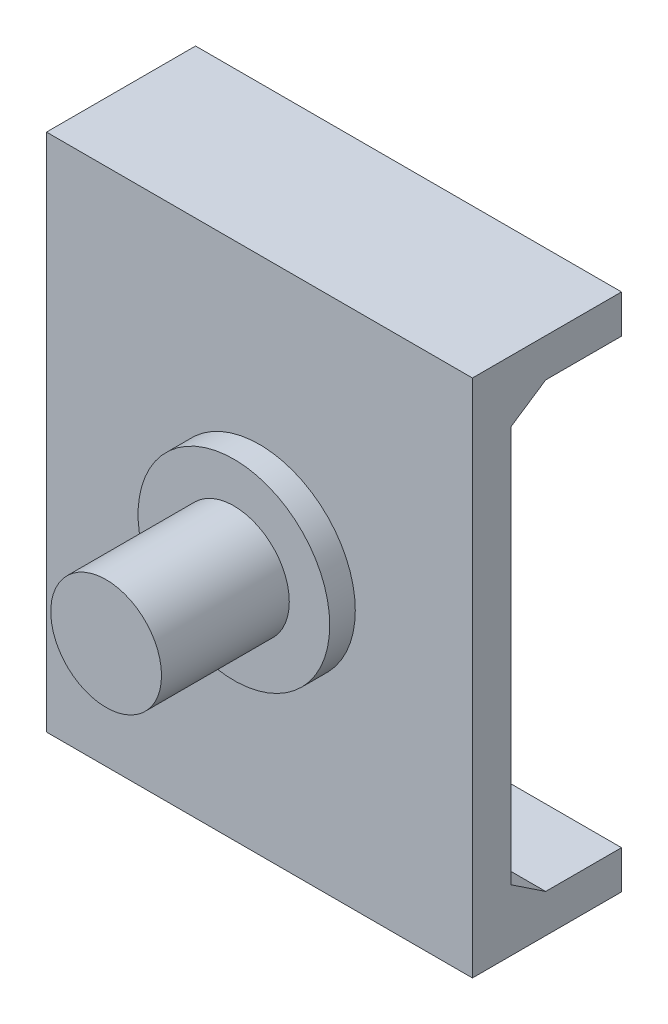
SolidWorks part; units mm, degrees
material "PETG"
ref_plane "Front Plane" through (0, 0, 0) normal (0, 0, 1) x (1, 0, 0)
ref_plane "Top Plane" through (0, 0, 0) normal (0, 1, 0) x (1, 0, 0)
ref_plane "Right Plane" through (0, 0, 0) normal (1, 0, 0) x (0, 0, -1)
sketch "Sketch1" plane through (0, 0, 0) normal (0, 0, 1) x (1, 0, 0)
  line L1 (-10, -12.2) -> (10, -12.2)
  line L2 (-10, -12.2) -> (-10, 12.2)
  line L3 (-10, 12.2) -> (10, 12.2)
  line L4 (10, -12.2) -> (10, 12.2)
  line L5 (-10, -12.2) -> (10, 12.2) construction
  line L6 (-10, 12.2) -> (10, -12.2) construction
  point P0 (0, 0)
  dimension "D2" = 20
extrude "Boss-Extrude1" add sketch "Sketch1" against normal blind 5 and the other way blind 2
sketch "Sketch3" plane through (10, 0, 0) normal (1, 0, 0) x (0, 0, -1)
  line L0 (1.5, 10.2) -> (8, 10.2) construction
  line L1 (1.5, 10.2) -> (0, 9.2) construction
  line L2 (0, 7.95) -> (0, 9.2) construction
  line L3 (0, 7.95) -> (0, 5.45) construction
  line L4 (0, -5.45) -> (0, 5.45) construction
  line L5 (0, -7.95) -> (0, -9.2) construction
  line L6 (0, -5.45) -> (0, -7.95) construction
  line L7 (0, -9.2) -> (1.5, -10.2) construction
  line L8 (8, -10.2) -> (1.5, -10.2) construction
  line L9 (1.5, 10.2) -> (8, 10.2) construction
  line L10 (1.5, 10.2) -> (0, 9.2) construction
  line L11 (0, 7.95) -> (0, 9.2) construction
  line L12 (0, 7.95) -> (0, 5.45) construction
  line L13 (0, -5.45) -> (0, 5.45) construction
  line L14 (0, -7.95) -> (0, -9.2) construction
  line L15 (0, -5.45) -> (0, -7.95) construction
  line L16 (0, -9.2) -> (1.5, -10.2) construction
  line L17 (8, -10.2) -> (1.5, -10.2) construction
  line L18 (8, -10.2) -> (8, 10.2) construction
  line L19 (8.2, -10.4) -> (1.4394, -10.4)
  line L20 (-0.2, -9.307) -> (1.4394, -10.4)
  line L21 (-0.2, -7.95) -> (-0.2, -9.307)
  line L22 (-0.2, -5.45) -> (-0.2, -7.95)
  line L23 (-0.2, -5.45) -> (-0.2, 5.45)
  line L24 (-0.2, 7.95) -> (-0.2, 5.45)
  line L25 (-0.2, 7.95) -> (-0.2, 9.307)
  line L26 (1.4394, 10.4) -> (-0.2, 9.307)
  line L27 (1.4394, 10.4) -> (8.2, 10.4)
  line L28 (8.2, -10.4) -> (8.2, 10.4)
  dimension "D1" = 0.2
extrude "Cut-Extrude1" cut sketch "Sketch3" against normal through all
sketch "Sketch4" plane through (0, 0, 2) normal (0, 0, 1) x (1, 0, 0)
  circle A0 centre (0, 0) radius 4.5
  dimension "D1" = 9
extrude "Boss-Extrude2" add sketch "Sketch4" along normal blind 1.2
sketch "Sketch5" plane through (0, 0, 3.2) normal (0, 0, 1) x (1, 0, 0)
  circle A0 centre (0, 0) radius 2.6
  dimension "D1" = 5.2
extrude "Boss-Extrude3" add sketch "Sketch5" along normal blind 6
